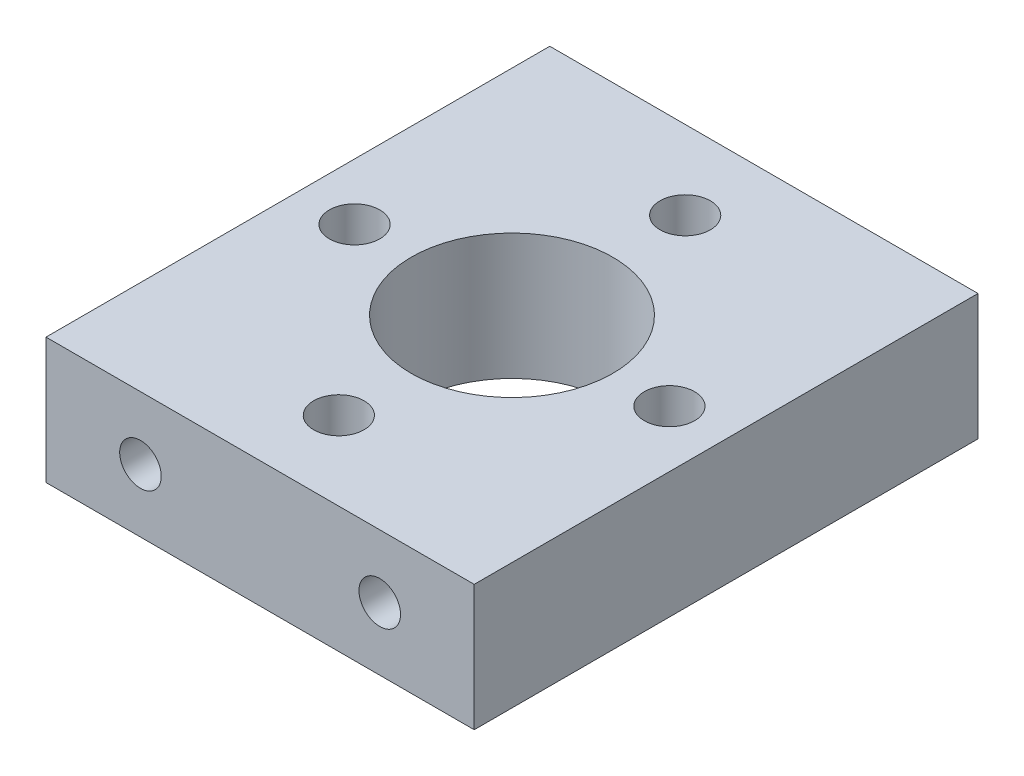
SolidWorks part; units mm, degrees
ref_plane "Front Plane" through (0, 0, 0) normal (0, 0, 1) x (1, 0, 0)
ref_plane "Top Plane" through (0, 0, 0) normal (0, 1, 0) x (1, 0, 0)
ref_plane "Right Plane" through (0, 0, 0) normal (1, 0, 0) x (0, 0, -1)
sketch "Sketch1" plane through (0, 0, 0) normal (0, 1, 0) x (1, 0, 0)
  line L0 (0, 20) -> (0, 0) construction
  line L1 (-17, -20) -> (17, -20)
  line L2 (-17, -20) -> (-17, 20)
  line L3 (-17, 20) -> (17, 20)
  line L4 (17, -20) -> (17, 20)
  line L5 (-17, -20) -> (17, 20) construction
  line L6 (-17, 20) -> (17, -20) construction
  line L7 (-17, 0) -> (-8, 0) construction
  line L8 (-12.5, 0) -> (12.5, 0) construction
  line L11 (0, 13.75) -> (0, -13.75) construction
  circle A0 centre (0, 0) radius 8
  circle A1 centre (0, 13.75) radius 2
  circle A2 centre (0, -13.75) radius 2
  circle A5 centre (-12.5, 0) radius 2
  circle A6 centre (12.5, 0) radius 2
  point P0 (0, 0)
  point P17 (-12.5, 0)
  point P19 (0, 0)
  point P23 (0, 0)
  dimension "D3" = 16
  dimension "D4" = 4
  dimension "D7" = 4
  dimension "D1" = 40
  dimension "D2" = 34
  dimension "D5" = 6.25
  dimension "D8" = 2
  dimension "D6" = 2
extrude "Boss-Extrude1" add sketch "Sketch1" along normal blind 10
hole_wizard "M4x0.7 Tapped Hole1" positions "3DSketch1" profile "Sketch2" tap size "M4x0.7" standard "ANSI Metric"
sketch3d "3DSketch1"
  line L0 (-17, 5, 20) -> (17, 5, 20) construction
  line L1 (-17, 10, 20) -> (-17, 0, 20) construction
  line L2 (17, 10, 20) -> (17, 0, 20) construction
  line L7 (-17, 5, -20) -> (-9.5, 5, -20) construction
  line L8 (-17, 10, -20) -> (-17, 0, -20) construction
  line L9 (-9.5, 5, -20) -> (9.5, 5, -20) construction
  line L10 (9.5, 5, -20) -> (17, 5, -20) construction
  line L11 (17, 10, -20) -> (17, 0, -20) construction
  point P0 (9.5, 5, -20)
  point P2 (-9.5, 5, -20)
  point P4 (-9.5, 5, 20)
  point P6 (9.5, 5, 20)
  dimension "D1" = 7.5
  dimension "D2" = 7.5
  dimension "D3" = 7.5
sketch "Sketch2" plane through (9.5, 5, -20) normal (1, 0, 0) x (0, 1, 0)
  line L0 (0, 0) -> (0, 15.9914)
  line L1 (0, 15.9914) -> (1.65, 15)
  line L2 (1.65, 15) -> (1.65, 0)
  line L5 (1.65, 0) -> (0, 0)
  line L10 (0, 15.9914) -> (-1.65, 15) construction
  line L11 (0, -6.35) -> (0, 107.95) construction
  dimension "Tap Drill Dia." = 3.3
  dimension "Tap Drill Depth" = 15
  dimension "Drill Angle" = 118
cosmetic thread "Hole Thread1" parameters "D1"=15, "D2"=4
cosmetic thread "Hole Thread2" parameters "D1"=15, "D2"=4
cosmetic thread "Hole Thread3" parameters "D1"=15, "D2"=4
cosmetic thread "Hole Thread4" parameters "D1"=15, "D2"=4
